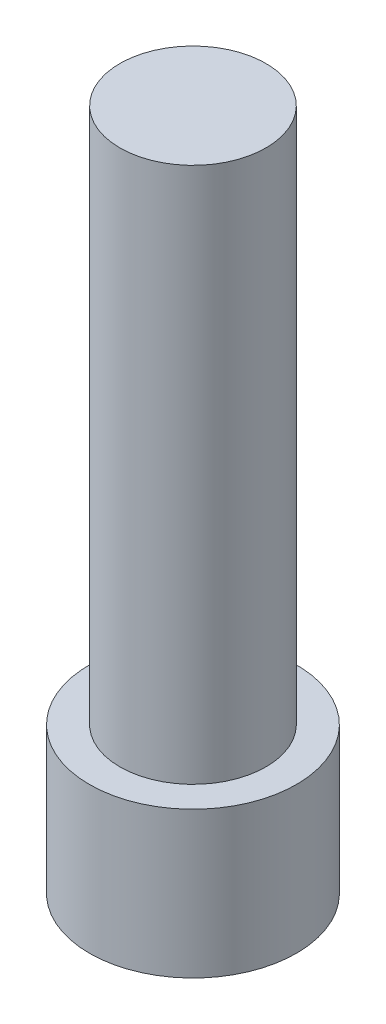
SolidWorks part; units mm, degrees
ref_plane "前视基准面" through (0, 0, 0) normal (0, 0, 1) x (1, 0, 0)
ref_plane "上视基准面" through (0, 0, 0) normal (0, 1, 0) x (1, 0, 0)
ref_plane "右视基准面" through (0, 0, 0) normal (1, 0, 0) x (0, 0, -1)
other "Configuration Table"
sketch "草图1" plane through (0, 0, 0) normal (0, 1, 0) x (1, 0, 0)
  circle A0 centre (0, 0) radius 4.25
  dimension "D1" = 8.5
extrude "凸台-拉伸1" add sketch "草图1" along normal blind 6
sketch "草图2" plane through (0, 6, 0) normal (0, 1, 0) x (1, 0, 0)
  circle A0 centre (0, 0) radius 3
  dimension "D1" = 6
extrude "凸台-拉伸2" add sketch "草图2" along normal blind 22
cosmetic thread "装饰螺纹线1"
sketch "草图3" plane through (0, 0, 0) normal (0, -1, 0) x (1, 0, 0)
  line L1 (2.3571, -1.6665) -> (2.6218, 1.2081)
  line L2 (2.6218, 1.2081) -> (0.2647, 2.8746)
  line L3 (0.2647, 2.8746) -> (-2.3571, 1.6665)
  line L4 (-2.3571, 1.6665) -> (-2.6218, -1.2081)
  line L5 (-2.6218, -1.2081) -> (-0.2647, -2.8746)
  line L6 (-0.2647, -2.8746) -> (2.3571, -1.6665)
  circle A0 centre (0, 0) radius 2.5 construction
  dimension "D1" = 5
extrude "切除-拉伸1" cut sketch "草图3" against normal blind 3
